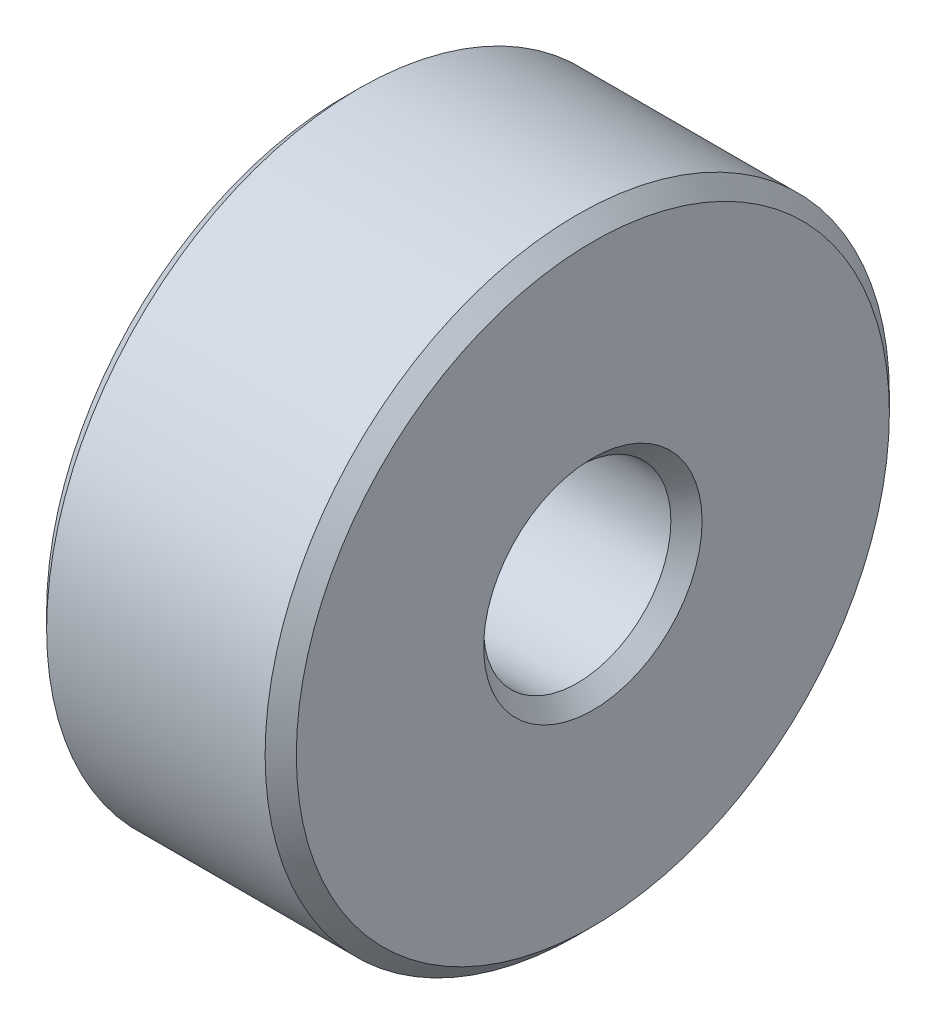
SolidWorks part; units mm, degrees
ref_plane "Front Plane" through (0, 0, 0) normal (0, 0, 1) x (1, 0, 0)
ref_plane "Top Plane" through (0, 0, 0) normal (0, 1, 0) x (1, 0, 0)
ref_plane "Right Plane" through (0, 0, 0) normal (1, 0, 0) x (0, 0, -1)
sketch "Sketch1" plane through (0, 0, 0) normal (1, 0, 0) x (0, 0, -1)
  circle A0 centre (0, 0) radius 5
  circle A1 centre (0, 0) radius 1.5
  dimension "D1" = 10
  dimension "D2" = 3
extrude "Boss-Extrude1" add sketch "Sketch1" along normal mid plane 4
chamfer "Chamfer1" distance 0.25 angle 45 3 edges at (2, 0, -1.5) (-2, 0, -5) (2, 0, -5)
